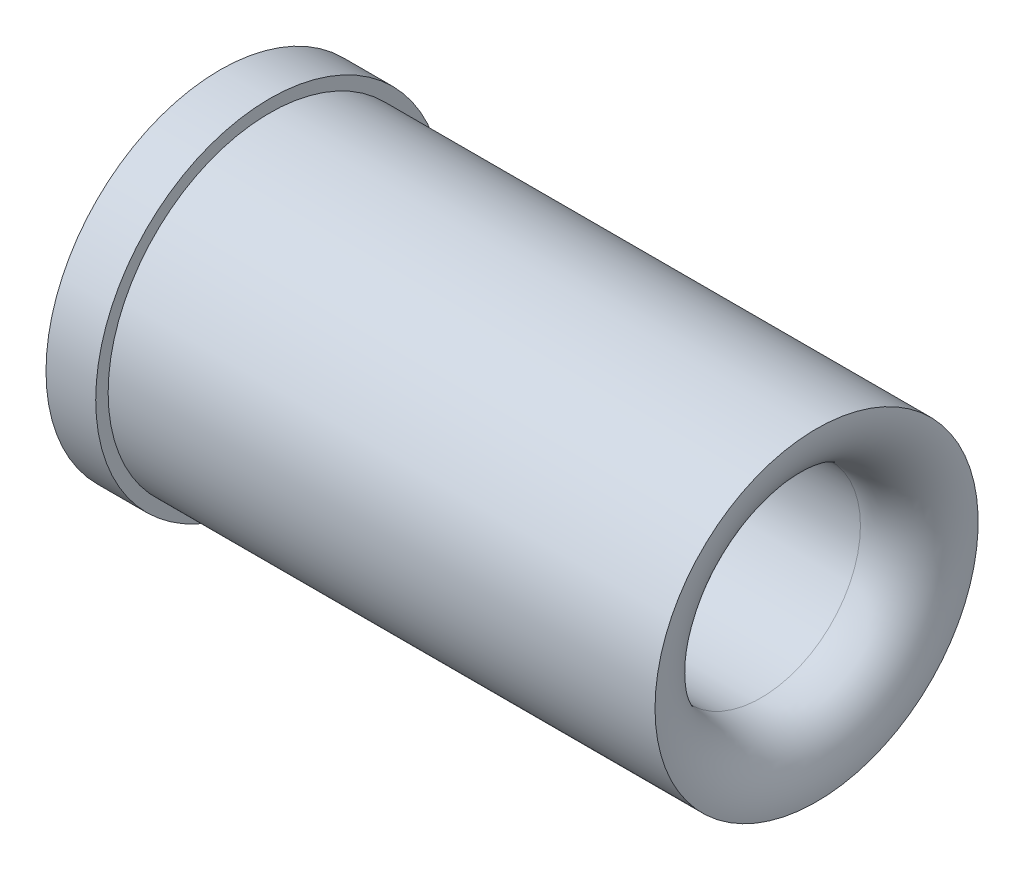
SolidWorks part; units mm, degrees
ref_plane "Front Plane" through (0, 0, 0) normal (0, 0, 1) x (1, 0, 0)
ref_plane "Top Plane" through (0, 0, 0) normal (0, 1, 0) x (1, 0, 0)
ref_plane "Right Plane" through (0, 0, 0) normal (1, 0, 0) x (0, 0, -1)
ref_plane "Plane1" through (0, 0, 0) normal (0, 0, -1) x (-1, 0, 0)
sketch "Sketch1" plane through (0, 0, 0) normal (0, 0, -1) x (-1, 0, 0)
  line L1 (-11.2941, -6.5333) -> (-0.9121, -6.5333)
  line L2 (-0.9121, -6.5333) -> (-0.9121, -5.0333)
  line L3 (-0.9121, -5.0333) -> (-1.9121, -5.0333)
  line L4 (-1.9121, -5.0333) -> (-1.9121, -5.2833)
  line L5 (-1.9121, -5.2833) -> (-12.9121, -5.2833)
  line L6 (-11.7941, -6.5333) -> (-11.2941, -6.5333)
  line L7 (-12.1757, -8.5333) -> (0.2029, -8.5333) construction
  arc A0 (-12.9121, -5.2833) -> (-11.7941, -6.5333) centre (-11.7941, -5.4083) ccw
  point P11 (0, 0)
  dimension "D1" = 11
  dimension "D2" = 7
  dimension "D3" = 0.25
  dimension "D4" = 2
  dimension "D6" = 1
  dimension "D7" = 0.5
revolve "Revolve1" add sketch "Sketch1" angle 360 about L7
